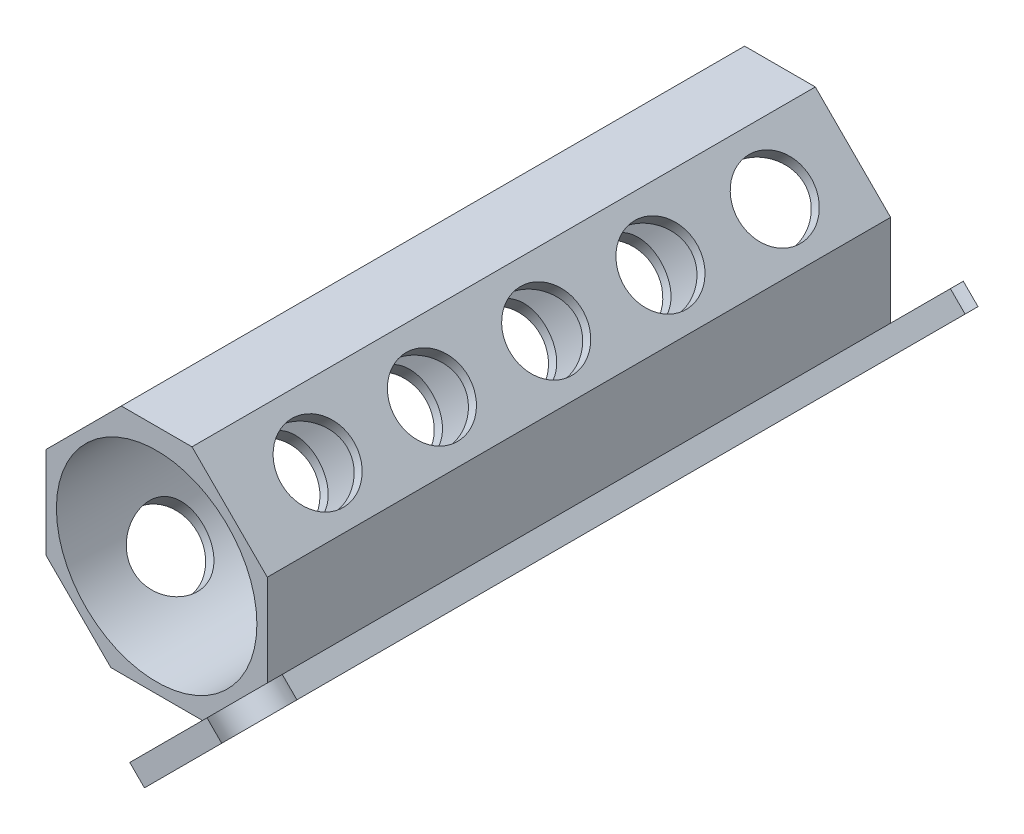
SolidWorks part; units mm, degrees
ref_plane "Ebene vorne" through (0, 0, 0) normal (1, 0, 0) x (0, 1, 0)
ref_plane "Ebene oben" through (0, 0, 0) normal (0, 0, 1) x (0, 1, 0)
ref_plane "Ebene rechts" through (0, 0, 0) normal (0, 1, 0) x (-1, 0, 0)
sketch "Skizze1" plane through (0, 0, 0) normal (0, 0, 1) x (0, 1, 0)
  line L0 (11.6589, 3.4025) -> (11.6589, -3.4025)
  line L13 (11.6589, 3.4025) -> (4.4114, 10.65)
  line L14 (4.4114, 10.65) -> (-4.4114, 10.65)
  line L15 (-4.4114, 10.65) -> (-10.65, 4.4114)
  line L16 (-10.65, 4.4114) -> (-10.65, -4.4114)
  line L17 (-10.65, -4.4114) -> (-4.4114, -10.65)
  line L18 (-4.4114, -10.65) -> (4.4114, -10.65)
  line L19 (4.4114, -10.65) -> (11.6589, -3.4025)
  line L29 (10.65, -1.6019) -> (10.65, 6.6409) [skipped]
  circle A0 centre (0, 0) radius 9.65
  circle A1 centre (0, 0) radius 10.65 construction
  dimension "D1" = 19.3
  dimension "D2" = 21.3
extrude "Aufsatz-Linear austragen1" add sketch "Skizze1" along normal blind 60
sketch "Skizze9" plane through (7.5307, 7.5307, 0) normal (0.7071, 0.7071, 0) x (-0.7071, 0.7071, 0)
  line L0 (0.7134, 60) -> (0.7134, 0) construction
  line L2 (-4.4114, 60) -> (5.8381, 60) construction
  line L3 (-4.4114, 0) -> (5.8381, 0) construction
  circle A0 centre (0.6135, 51.6) radius 3.5
  circle A1 centre (0.6135, 40.6) radius 3.5
  circle A2 centre (0.6135, 29.6) radius 3.5
  circle A3 centre (0.6135, 18.6) radius 3.5
  circle A4 centre (0.6135, 7.6) radius 3.5
  dimension "D1" = 7
  dimension "D2" = 5
extrude "Schnitt-Linear austragen8" cut sketch "Skizze9" against normal through all
sketch "Skizze13" plane through (7.5307, -7.5307, 0) normal (0.7071, -0.7071, 0) x (0.7071, 0.7071, 0)
  line L0 (0, 60) -> (0, 0) construction
  line L1 (-9.5, -6.4) -> (9.5, -6.4)
  line L2 (-9.5, -6.4) -> (-9.5, 66.4)
  line L3 (-9.5, 66.4) -> (9.5, 66.4)
  line L4 (9.5, -6.4) -> (9.5, 66.4)
  line L5 (-9.5, -6.4) -> (9.5, 66.4) construction
  line L6 (-9.5, 66.4) -> (9.5, -6.4) construction
  line L7 (-4.4114, 60) -> (4.4114, 60) construction
  point P0 (0, 30)
  point P11 (0, 30)
  dimension "D1" = 19
  dimension "D2" = 72.8
extrude "Aufsatz-Linear austragen2" add sketch "Skizze13" along normal blind 2
sketch "Skizze14" plane through (8.9449, -8.9449, 0) normal (0.7071, -0.7071, 0) x (0.7071, 0.7071, 0)
  circle A0 centre (7.38, 64.28) radius 3
  circle A2 centre (-7.38, -4.28) radius 3
  circle A3 centre (7.38, -4.28) radius 3
  circle A4 centre (-7.38, 64.28) radius 3
  dimension "D1" = 6
  dimension "D2" = 2.12
  dimension "D3" = 6
  dimension "D4" = 6
  dimension "D8" = 6
  dimension "D5" = 2.12
  dimension "D6" = 2.12
  dimension "D7" = 2.12
  dimension "D9" = 2.12
  dimension "D10" = 2.12
  dimension "D11" = 2.12
  dimension "D12" = 2.12
extrude "Schnitt-Linear austragen12" cut sketch "Skizze14" against normal blind 2
